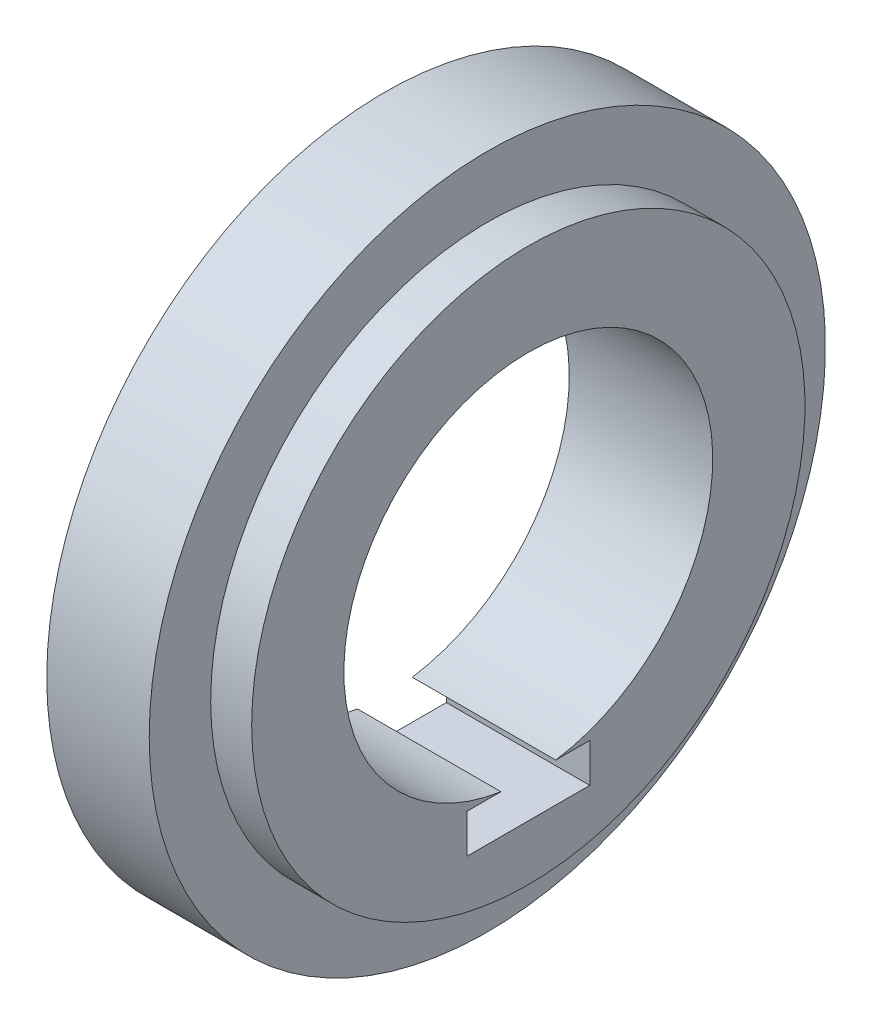
SolidWorks part; units mm, degrees
material "普通碳钢"
ref_plane "前视基准面" through (0, 0, 0) normal (0, 0, 1) x (1, 0, 0)
ref_plane "上视基准面" through (0, 0, 0) normal (0, 1, 0) x (1, 0, 0)
ref_plane "右视基准面" through (0, 0, 0) normal (1, 0, 0) x (0, 0, -1)
other "Configuration Table"
sketch "草图1" plane through (0, 0, 0) normal (0, 0, 1) x (1, 0, 0)
  line L0 (0, 9) -> (0, 16.5)
  line L1 (0, 16.5) -> (5, 16.5)
  line L2 (5, 16.5) -> (5, 13.5)
  line L3 (5, 13.5) -> (7, 13.5)
  line L4 (7, 13.5) -> (7, 9)
  line L5 (7, 9) -> (0, 9)
  line L6 (-3, 0) -> (10, 0) construction
revolve "旋转1" add sketch "草图1" angle 360 about L6
sketch "草图2" plane through (0, 0, 0) normal (1, 0, 0) x (0, 0, -1)
  line L1 (-3, -10.8) -> (3, -10.8)
  line L2 (-3, -10.8) -> (-3, -8.9)
  line L3 (-3, -8.9) -> (3, -8.9)
  line L4 (3, -10.8) -> (3, -8.9)
extrude "02_KEYWAY" cut sketch "草图2" along normal through all
